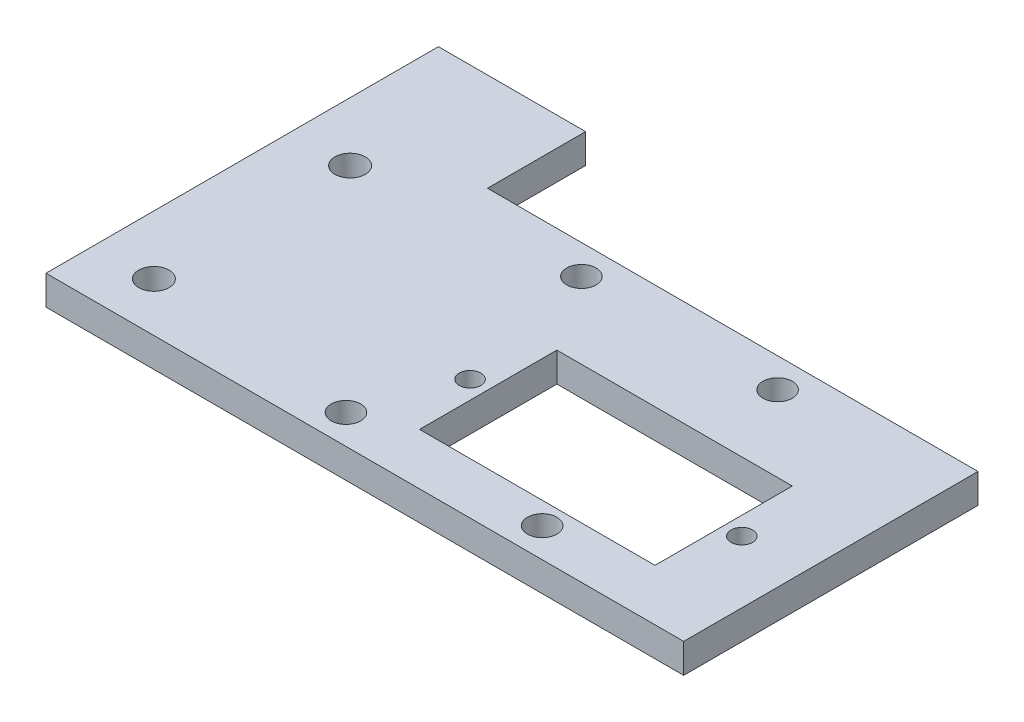
SolidWorks part; units mm, degrees
ref_plane "前视基准面" through (0, 0, 0) normal (0, 0, 1) x (1, 0, 0)
ref_plane "上视基准面" through (0, 0, 0) normal (0, 1, 0) x (1, 0, 0)
ref_plane "右视基准面" through (0, 0, 0) normal (1, 0, 0) x (0, 0, -1)
sketch "草图1" plane through (0, 0, 0) normal (0, 1, 0) x (1, 0, 0)
  line L0 (0, 20) -> (0, -20) construction
  line L1 (-32.5, 20) -> (32.5, 20)
  line L2 (-32.5, 20) -> (-32.5, -20)
  line L3 (-32.5, -20) -> (32.5, -20)
  line L4 (32.5, 20) -> (32.5, -20)
  line L5 (-32.5, 20) -> (32.5, -20) construction
  line L6 (-32.5, -20) -> (32.5, 20) construction
  point P0 (0, 0)
  dimension "D1" = 40
  dimension "D2" = 65
extrude "凸台-拉伸1" add sketch "草图1" along normal blind 3
ref_plane "基准面1" through (0, 0, 0) normal (0, -1, 0) x (-1, 0, 0)
ref_plane "基准面2" through (0, 0, 0) normal (0, -1, 0) x (-1, 0, 0)
sketch "草图2" plane through (0, 0, 0) normal (0, -1, 0) x (-1, 0, 0)
  line L0 (26.5, -20) -> (26.5, -15) construction
  line L1 (32.5, -20) -> (-32.5, -20) construction
  line L2 (26.5, -15) -> (26.5, 5) construction
  line L3 (32.5, 20) -> (32.5, -20) construction
  circle A0 centre (26.5, -15) radius 1.55
  circle A1 centre (26.5, 5) radius 1.55
  dimension "D1" = 3.1
  dimension "D2" = 3.1
  dimension "D3" = 6
  dimension "D4" = 5
  dimension "D5" = 20
extrude "切除-拉伸1" cut sketch "草图2" against normal blind 10
sketch "草图3" plane through (0, 0, 0) normal (0, -1, 0) x (-1, 0, 0)
  line L1 (-32.5, 20) -> (17.5, 20)
  line L2 (-32.5, 20) -> (-32.5, 10)
  line L3 (-32.5, 10) -> (17.5, 10)
  line L4 (17.5, 20) -> (17.5, 10)
  dimension "D1" = 10
  dimension "D2" = 50
extrude "切除-拉伸2" cut sketch "草图3" against normal blind 10
ref_plane "基准面3" through (0, 0, 0) normal (0, -1, 0) x (-1, 0, 0)
sketch "草图4" plane through (0, 0, 0) normal (0, -1, 0) x (-1, 0, 0)
  line L0 (-23.8249, -1.5) -> (-0.8249, -14) construction
  line L2 (-24.3249, -0.75) -> (-0.3249, -0.75)
  line L3 (-24.3249, -0.75) -> (-24.3249, -14.75)
  line L4 (-24.3249, -14.75) -> (-0.3249, -14.75)
  line L5 (-0.3249, -0.75) -> (-0.3249, -14.75)
  line L6 (-24.3249, -0.75) -> (-0.3249, -14.75) construction
  line L7 (-24.3249, -14.75) -> (-0.3249, -0.75) construction
  point P4 (-12.3249, -7.75)
  dimension "D1" = 24
  dimension "D2" = 14
extrude "切除-拉伸3" cut sketch "草图4" against normal blind 10
ref_plane "基准面4" through (0, 3, 0) normal (0, 1, 0) x (1, 0, 0)
sketch "草图5" plane through (0, 3, 0) normal (0, 1, 0) x (1, 0, 0)
  circle A0 centre (26.1749, -7.75) radius 1.1
  circle A1 centre (-1.5251, -7.75) radius 1.1
  dimension "D1" = 2.2
  dimension "D2" = 2.2
extrude "切除-拉伸4" cut sketch "草图5" against normal blind 10
sketch "草图6" plane through (0, 0, 0) normal (0, -1, 0) x (-1, 0, 0)
  circle A0 centre (-15.075, -17) radius 1.5
  circle A1 centre (4.925, -17) radius 1.5
  circle A2 centre (-15.075, 7) radius 1.5
  circle A3 centre (4.925, 7) radius 1.5
extrude "切除-拉伸5" cut sketch "草图6" against normal blind 25
